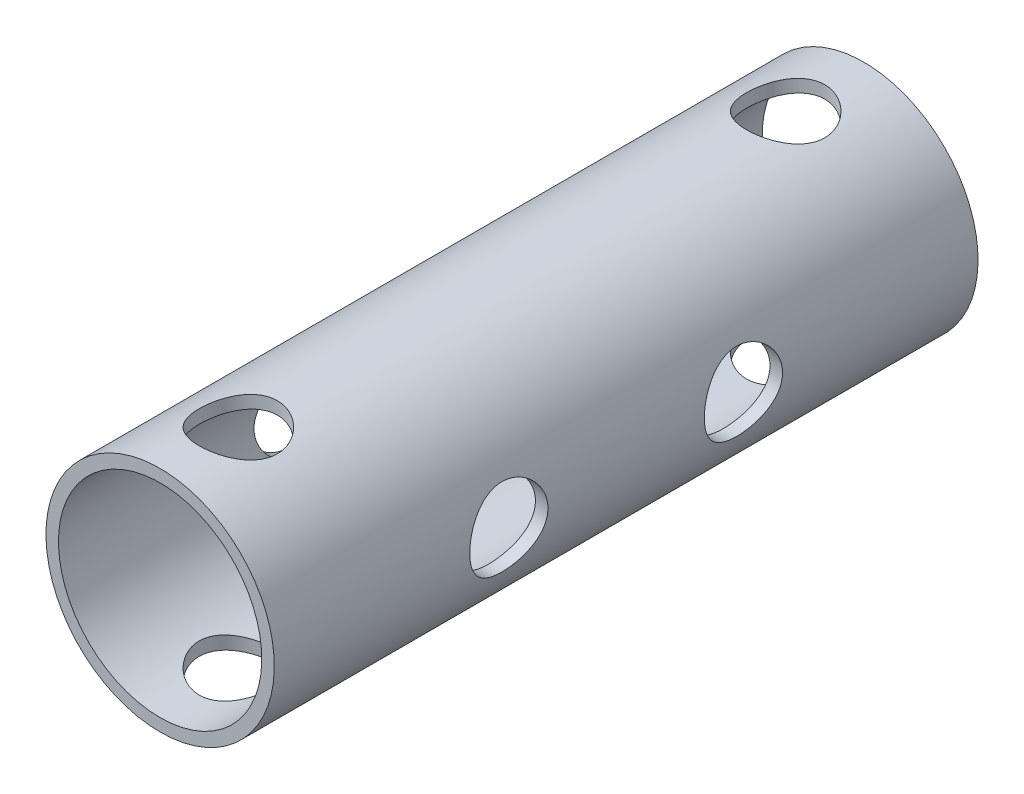
SolidWorks part; units mm, degrees
ref_plane "Front Plane" through (0, 0, 0) normal (0, 0, 1) x (1, 0, 0)
ref_plane "Top Plane" through (0, 0, 0) normal (0, 1, 0) x (1, 0, 0)
ref_plane "Right Plane" through (0, 0, 0) normal (1, 0, 0) x (0, 0, -1)
sketch "Sketch15" plane through (0, 0, 0) normal (1, 0, 0) x (0, 0, -1)
  line L0 (45, 0) -> (-45, 0)
  point P3 (-5, 0)
  point P5 (5, 0)
  dimension "D1" = 90
  dimension "D2" = 40
  dimension "D3" = 40
other "Pipe 25.4 X 1.6(2)"
ref_plane "Plane6" through (0, 0, -45) normal (0, 0, 1) x (0, -1, 0)
sketch "Sketch1" plane through (0, 0, -45) normal (0, 0, 1) x (0, -1, 0)
  circle A0 centre (0, 0) radius 13
  circle A1 centre (0, 0) radius 14.6
  point P3 (0, 0)
  dimension "D1" = 1.6
  dimension "D2" = 26
sketch "Sketch16" plane through (0, 0, 0) normal (1, 0, 0) x (0, 0, -1)
  line L0 (45, 0) -> (-45, 0) construction
  circle A0 centre (-15, 0) radius 5
  circle A1 centre (15, 0) radius 5
  dimension "D1" = 10
  dimension "D2" = 10
  dimension "D3" = 10
extrude "Cut-Extrude4" cut sketch "Sketch16" against normal mid plane 60
sketch "Sketch17" plane through (0, 0, 0) normal (0, 1, 0) x (1, 0, 0)
  line L0 (0, 45) -> (0, -45) construction
  line L1 (13, 45) -> (-13, 45) construction
  line L2 (-14.6, -45) -> (14.6, -45) construction
  circle A0 centre (0, -35) radius 5
  circle A1 centre (0, 35) radius 5
  dimension "D1" = 10
  dimension "D2" = 10
  dimension "D3" = 10
extrude "Cut-Extrude5" cut sketch "Sketch17" against normal mid plane 60
